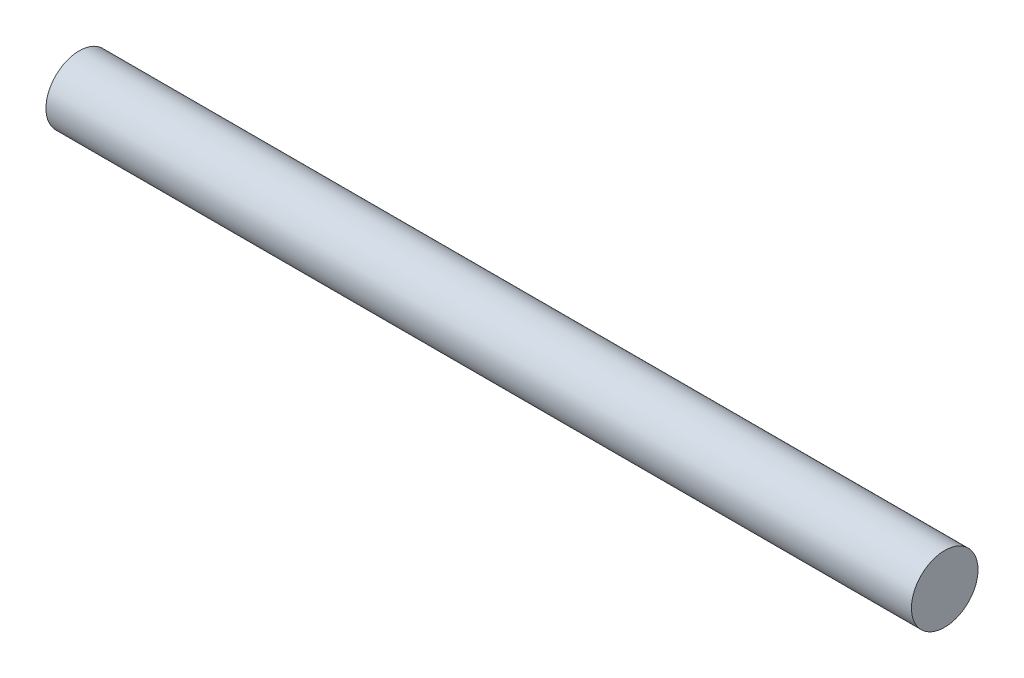
SolidWorks part; units mm, degrees
ref_plane "Front" through (0, 0, 0) normal (0, 0, 1) x (1, 0, 0)
ref_plane "Top" through (0, 0, 0) normal (0, 1, 0) x (1, 0, 0)
ref_plane "Right" through (0, 0, 0) normal (1, 0, 0) x (0, 0, -1)
sketch "Sketch1" plane through (0, 0, 0) normal (1, 0, 0) x (0, 0, -1)
  circle A0 centre (0, 0) radius 0.5
  dimension "D1" = 1
extrude "Boss-Extrude1" add sketch "Sketch1" along normal blind 13
